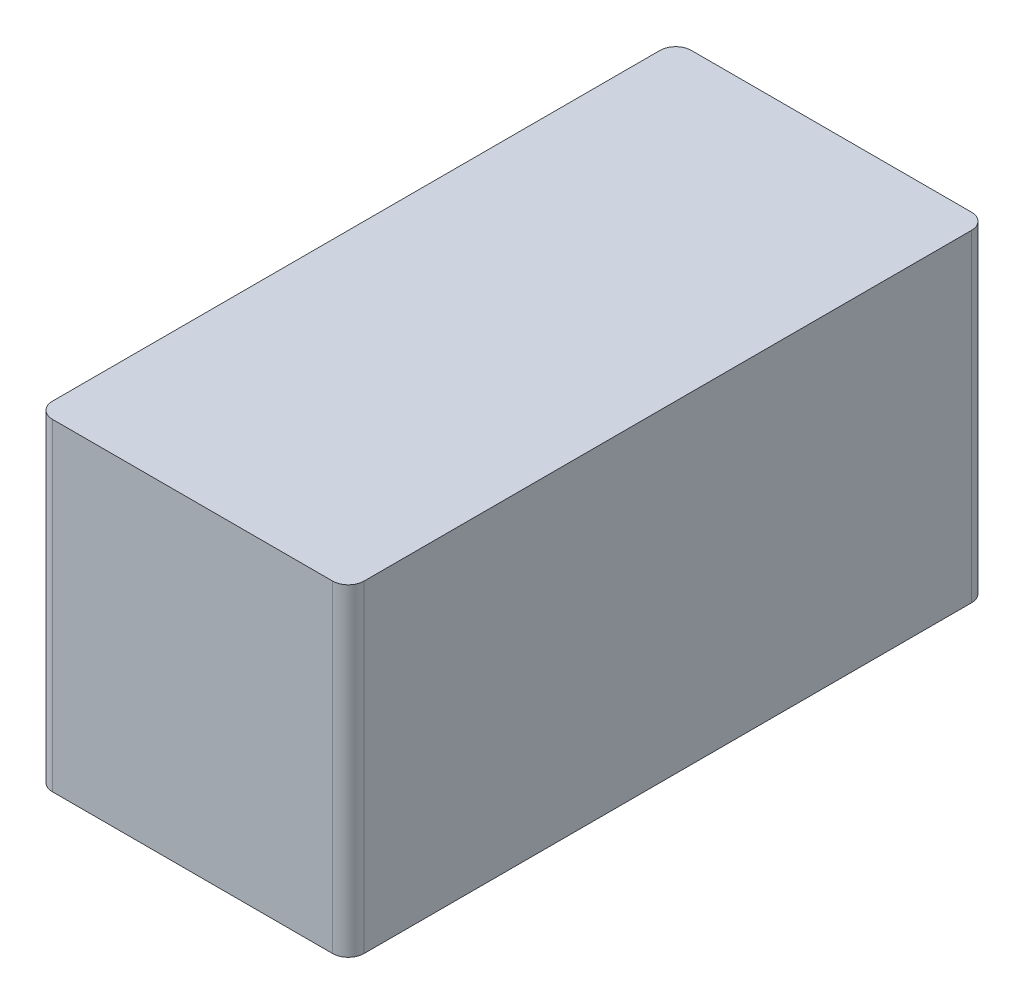
SolidWorks part; units mm, degrees
material "Polyethylene Cross-Linked"
ref_plane "Front Plane" through (0, 0, 0) normal (0, 0, 1) x (1, 0, 0)
ref_plane "Top Plane" through (0, 0, 0) normal (0, 1, 0) x (1, 0, 0)
ref_plane "Right Plane" through (0, 0, 0) normal (1, 0, 0) x (0, 0, -1)
sketch "Sketch1" plane through (0, 0, 0) normal (0, 1, 0) x (1, 0, 0)
  line L1 (-9.9, 20.3) -> (9.9, 20.3)
  line L2 (-9.9, 20.3) -> (-9.9, -20.3)
  line L3 (-9.9, -20.3) -> (9.9, -20.3)
  line L4 (9.9, 20.3) -> (9.9, -20.3)
  line L5 (-9.9, 20.3) -> (9.9, -20.3) construction
  line L6 (-9.9, -20.3) -> (9.9, 20.3) construction
  point P0 (0, 0)
  dimension "D1" = 19.8
  dimension "D2" = 40.6
extrude "Boss-Extrude1" add sketch "Sketch1" along normal mid plane 20.5
fillet "Fillet1" radius 1 4 edges at (-9.9, 0, -20.3) (9.9, 0, -20.3) (9.9, 0, 20.3) (-9.9, 0, 20.3)
move or copy body "Body-Move/Copy1" [suppressed] bodies to move or copy 132
move or copy body "Body-Move/Copy2" [suppressed] bodies to move or copy 133
